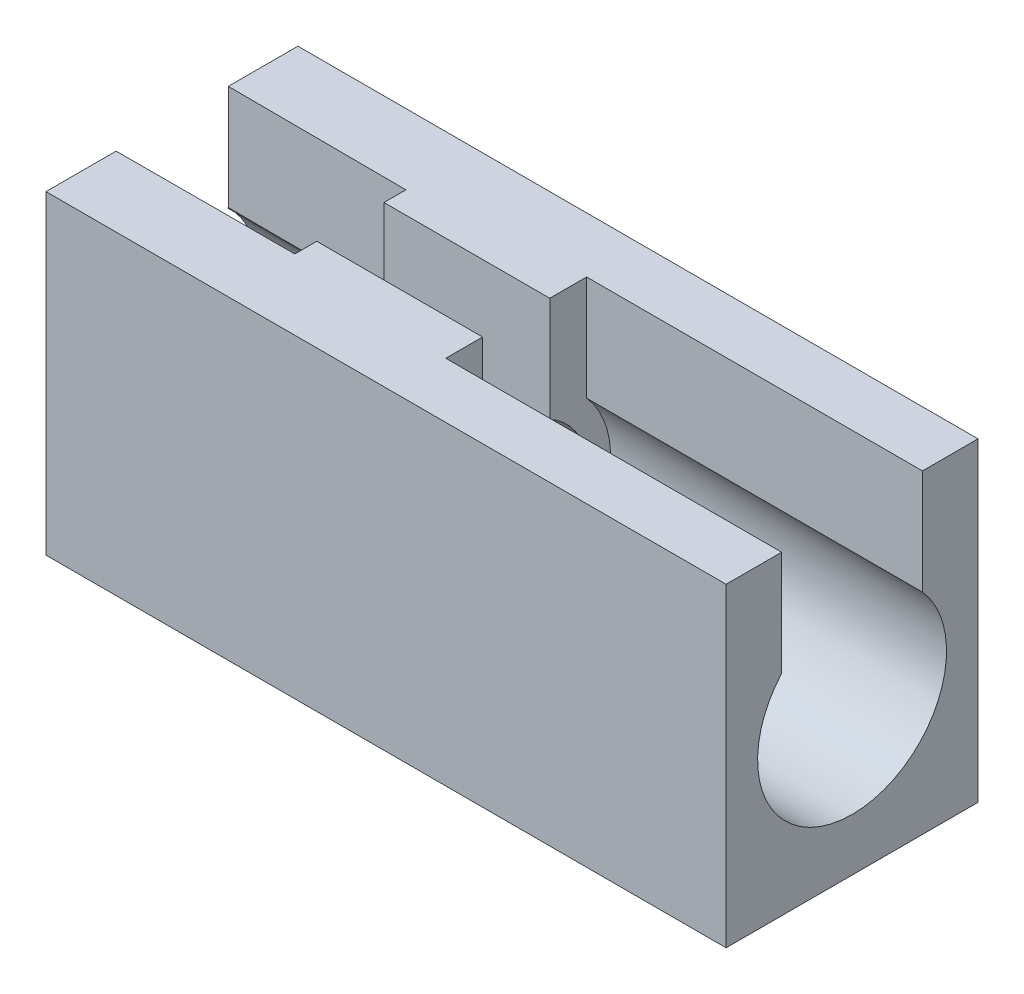
SolidWorks part; units mm, degrees
ref_plane "前基準面" through (0, 0, 0) normal (0, 0, 1) x (1, 0, 0)
ref_plane "上基準面" through (0, 0, 0) normal (0, 1, 0) x (1, 0, 0)
ref_plane "右基準面" through (0, 0, 0) normal (1, 0, 0) x (0, 0, -1)
sketch "草圖1" plane through (0, 0, 0) normal (0, 1, 0) x (1, 0, 0)
  line L1 (-16.2, 6) -> (16.2, 6)
  line L2 (-16.2, 6) -> (-16.2, -6)
  line L3 (-16.2, -6) -> (16.2, -6)
  line L4 (16.2, 6) -> (16.2, -6)
  line L5 (-16.2, 6) -> (16.2, -6) construction
  line L6 (-16.2, -6) -> (16.2, 6) construction
  point P0 (0, 0)
  dimension "D1" = 32.4
  dimension "D2" = 12
extrude "填料-伸長1" add sketch "草圖1" along normal blind 10
sketch "草圖3" plane through (-16.2, 0, 0) normal (-1, 0, 0) x (0, 0, 1)
  line L0 (0, -1000) -> (0, 49000) construction
  line L1 (-6, 10) -> (6, 10) construction
  line L2 (0, 10) -> (-1.142, 10) construction
  line L3 (0, 10) -> (0, 7) construction
  line L4 (0, 7) -> (-1.142, 7) construction
  line L5 (-1.142, 10) -> (-1.142, 7) construction
  line L6 (-1001.142, 7) -> (48998.858, 7) construction
  dimension "D1" = 3
sketch "草圖4" plane through (-16.2, 0, 0) normal (-1, 0, 0) x (0, 0, 1)
  circle A0 centre (0, 7) radius 4
  dimension "D1" = 8
extrude "除料-伸長2" cut sketch "草圖4" against normal blind 8.5
ref_plane "平面2" through (-16.2, 0, 0) normal (-1, 0, 0) x (0, 0, 1)
sketch "草圖6" plane through (-16.2, 0, 0) normal (-1, 0, 0) x (0, 0, 1)
  circle A0 centre (0, 7) radius 4
curve "螺旋曲線/渦捲線2" pitch 0.4054 height 8.5135 turns 21
sketch "草圖7" plane through (-7.7, 0, 0) normal (-1, 0, 0) x (0, 0, 1)
  circle A0 centre (0, 7) radius 3.4
  dimension "D1" = 6.8
extrude "除料-伸長3" cut sketch "草圖7" against normal blind 7.9
sketch "草圖8" plane through (16.2, 0, 0) normal (1, 0, 0) x (0, 0, -1)
  circle A0 centre (0, 7) radius 4.5
  dimension "D1" = 9
extrude "除料-伸長4" cut sketch "草圖8" against normal blind 16
sketch "草圖9" plane through (0, 10, 0) normal (0, 1, 0) x (1, 0, 0)
  line L0 (-16.2, 201001.142) -> (-16.2, -248998.858) construction
  line L1 (-16.2, 6) -> (16.2, 6)
  line L2 (-16.2, 6) -> (-16.2, 3.3541)
  line L3 (-16.2, 3.3541) -> (16.2, 3.3541)
  line L4 (16.2, 6) -> (16.2, 3.3541)
  line L5 (16.2, 6) -> (-16.2, 6) construction
extrude "填料-伸長2" add sketch "草圖9" along normal blind 5
sketch "草圖10" plane through (0, 10, 0) normal (0, 1, 0) x (1, 0, 0)
  line L0 (-16.2, 3.3725) -> (-16.2, 2.6855)
  line L1 (-16.2, 201001.142) -> (-16.2, -248998.858) construction
  line L2 (-16.2, 2.6855) -> (-7.7, 2.6458)
  line L3 (-7.7, 2.6458) -> (-7.7, 1.6)
  line L4 (-7.7, 4) -> (-7.7, -4) construction
  line L5 (-7.7, 3.4) -> (-7.7, -3.4) construction
  line L6 (-7.7, 1.6) -> (0.2, 1.6)
  line L7 (0.2, -4.5) -> (0.2, 4.5) construction
  line L8 (0.2, 1.6) -> (-7.7, 1.6) construction
  line L9 (0.2, 1.6) -> (0.2, 3.3541)
  line L10 (0.2, 3.3541) -> (-16.2, 3.3725)
extrude "填料-伸長3" add sketch "草圖10" along normal blind 5
sketch "草圖11" plane through (0, 10, 0) normal (0, 1, 0) x (1, 0, 0)
  line L0 (-16.2, -2.6607) -> (-16.2, -6)
  line L1 (-16.2, 201001.142) -> (-16.2, -248998.858) construction
  line L2 (-16.2, -6) -> (16.2, -6) construction
  line L3 (-16.2, -6) -> (16.2, -6)
  line L4 (16.2, -6) -> (16.2, -3.3541)
  line L5 (16.2, -3.3541) -> (0.2, -3.3541)
  line L6 (0.2, -3.3541) -> (0.2, -1.6)
  line L7 (0.2, -1.6) -> (-7.7, -1.6)
  line L8 (-7.7, -1.6) -> (-7.7, -2.6458)
  line L9 (-7.7, -2.6458) -> (-16.2, -2.6607)
extrude "填料-伸長4" add sketch "草圖11" along normal blind 5
